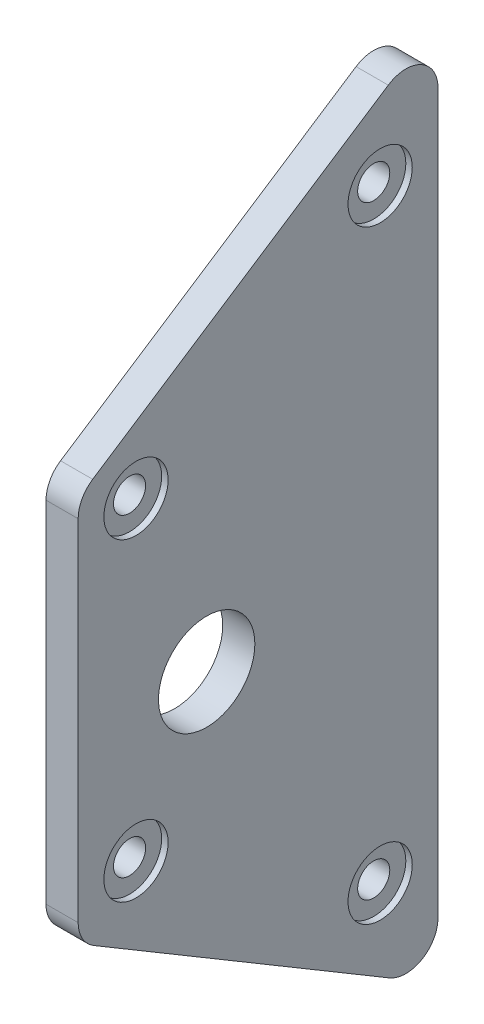
SolidWorks part; units mm, degrees
ref_plane "Front Plane" through (0, 0, 0) normal (0, 0, 1) x (1, 0, 0)
ref_plane "Top Plane" through (0, 0, 0) normal (0, 1, 0) x (1, 0, 0)
ref_plane "Right Plane" through (0, 0, 0) normal (1, 0, 0) x (0, 0, -1)
sketch "Sketch2" plane through (0, 0, 0) normal (1, 0, 0) x (0, 0, -1)
  line L0 (-30.5706, 35.9644) -> (-30.5706, -40.2356)
  line L1 (-30.5706, -40.2356) -> (40.5494, -82.55)
  line L2 (40.5494, -82.55) -> (40.5494, 82.55)
  line L3 (40.5494, 82.55) -> (-30.5706, 35.9644)
  line L4 (40.5494, 82.55) -> (-30.5706, 82.55) construction
  line L5 (40.5494, -82.55) -> (-40.5494, -82.55) construction
  circle A0 centre (29.1194, 59.69) radius 3.175
  circle A1 centre (-19.1406, 30.2927) radius 3.175
  circle A2 centre (29.1194, -59.69) radius 3.175
  circle A3 centre (-19.1406, -31.75) radius 3.175
  circle A4 centre (-5.1706, -6.35) radius 9.525
  dimension "D4" = 6.35
  dimension "D5" = 6.35
  dimension "D6" = 6.35
  dimension "D7" = 6.35
  dimension "D8" = 19.05
  dimension "D1" = 76.2
  dimension "D2" = 71.12
  dimension "D3" = 165.1
  dimension "D9" = 11.43
  dimension "D10" = 11.43
  dimension "D11" = 52.2573
  dimension "D12" = 50.8
  dimension "D13" = 11.43
  dimension "D14" = 11.43
  dimension "D15" = 25.4
  dimension "D16" = 76.2
extrude "Boss-Extrude1" add sketch "Sketch2" along normal blind 6.35
ref_plane "Plane1" through (6.35, 0, 0) normal (1, 0, 0) x (0, 0, -1)
sketch "Sketch3" plane through (6.35, 0, 0) normal (1, 0, 0) x (0, 0, -1)
  circle A0 centre (-19.1406, 30.2927) radius 6.35
  circle A1 centre (29.1194, 59.69) radius 6.35
  circle A2 centre (-19.1406, -31.75) radius 6.35
  circle A3 centre (29.1194, -59.69) radius 6.35
  dimension "D1" = 12.7
  dimension "D2" = 12.7
  dimension "D3" = 12.7
  dimension "D4" = 12.7
extrude "Cut-Extrude1" cut sketch "Sketch3" against normal blind 1.27
fillet "Fillet1" radius 6.35 4 edges at (3.175, -82.55, -40.5494) (3.175, -40.2356, 30.5706) (3.175, 35.9644, 30.5706) (3.175, 82.55, -40.5494)
